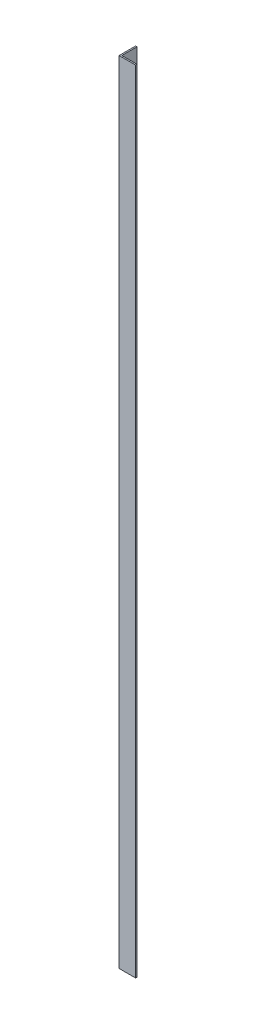
SolidWorks part; units mm, degrees
ref_plane "Front Plane" through (0, 0, 0) normal (0, 0, 1) x (1, 0, 0)
ref_plane "Top Plane" through (0, 0, 0) normal (0, 1, 0) x (1, 0, 0)
ref_plane "Right Plane" through (0, 0, 0) normal (1, 0, 0) x (0, 0, -1)
sketch "Sketch1" plane through (0, 0, 0) normal (0, 1, 0) x (1, 0, 0)
  line L0 (0, 0) -> (0, -19.05)
  line L1 (0, -19.05) -> (19.05, -19.05)
  line L2 (0, 0) -> (1.5875, 0)
  line L3 (19.05, -19.05) -> (19.05, -17.4625)
  line L4 (19.05, -17.4625) -> (1.5875, -17.4625)
  line L5 (1.5875, -17.4625) -> (1.5875, 0)
  dimension "D1" = 19.05
  dimension "D2" = 19.05
  dimension "D3" = 1.5875
  dimension "D4" = 1.5875
extrude "Boss-Extrude1" add sketch "Sketch1" along normal blind 914.4
